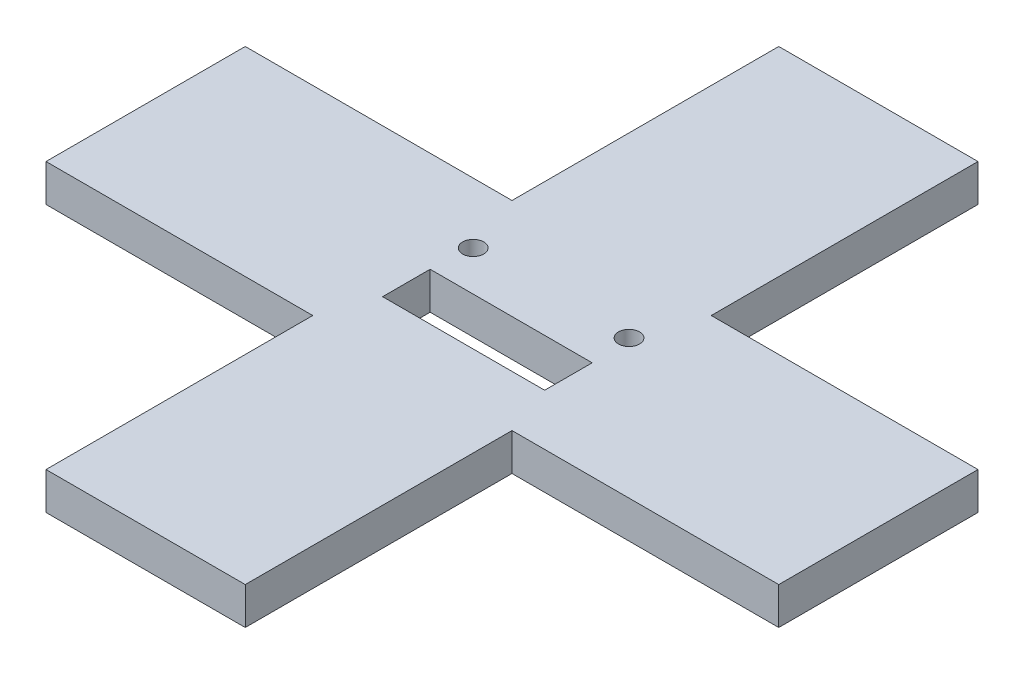
SolidWorks part; units mm, degrees
ref_plane "Front Plane" through (0, 0, 0) normal (0, 0, 1) x (1, 0, 0)
ref_plane "Top Plane" through (0, 0, 0) normal (0, 1, 0) x (1, 0, 0)
ref_plane "Right Plane" through (0, 0, 0) normal (1, 0, 0) x (0, 0, -1)
sketch "Sketch21" plane through (0, 0, 0) normal (0, 1, 0) x (1, 0, 0)
  line L22 (-0.0028, 59.1997) -> (-16.0628, 59.1997)
  line L23 (-16.0628, 59.1997) -> (-16.0628, 16.1997)
  line L24 (-16.0628, 16.1997) -> (-59.0628, 16.1997)
  line L25 (-59.0628, -15.9203) -> (-16.0628, -15.9203)
  line L26 (-16.0628, -15.9203) -> (-16.0628, -58.9203)
  line L27 (-16.0628, -58.9203) -> (-0.0028, -58.9203)
  line L28 (-0.0028, -58.9203) -> (16.0572, -58.9203)
  line L29 (16.0572, -58.9203) -> (16.0572, -15.9203)
  line L30 (16.0572, -15.9203) -> (59.0572, -15.9203)
  line L31 (59.0572, 16.1997) -> (16.0572, 16.1997)
  line L32 (16.0572, 16.1997) -> (16.0572, 59.1997)
  line L33 (16.0572, 59.1997) -> (-0.0028, 59.1997)
  line L34 (-59.0628, 0.1397) -> (-59.0628, 16.1997)
  line L35 (-59.0628, -15.9203) -> (-59.0628, 0.1397)
  line L36 (59.0572, 0.1397) -> (59.0572, 16.1997)
  line L37 (59.0572, 0.1397) -> (59.0572, -15.9203)
  line L38 (13.06, -7.66) -> (-13.06, -7.66)
  line L39 (13.06, -7.66) -> (13.06, 0)
  line L40 (13.06, 0) -> (-13.06, 0)
  line L41 (-13.06, -7.66) -> (-13.06, 0)
  line L42 (13.06, -7.66) -> (-13.06, 0) construction
  line L43 (13.06, 0) -> (-13.06, -7.66) construction
  circle A0 centre (-12.56, 6.44) radius 1.7
  circle A1 centre (12.56, 6.44) radius 1.7
  point P16 (0, -3.83)
  dimension "D7" = 3.4
  dimension "D9" = 12.56
  dimension "D10" = 6.44
  dimension "D1" = 43
  dimension "D2" = 16.06
  dimension "D3" = 26.12
  dimension "D4" = 7.66
  dimension "D5" = 0
  dimension "D6" = 3.83
  dimension "D8" = 12.56
  dimension "D11" = 6.44
extrude "Boss-Extrude18" add sketch "Sketch21" along normal blind 6
